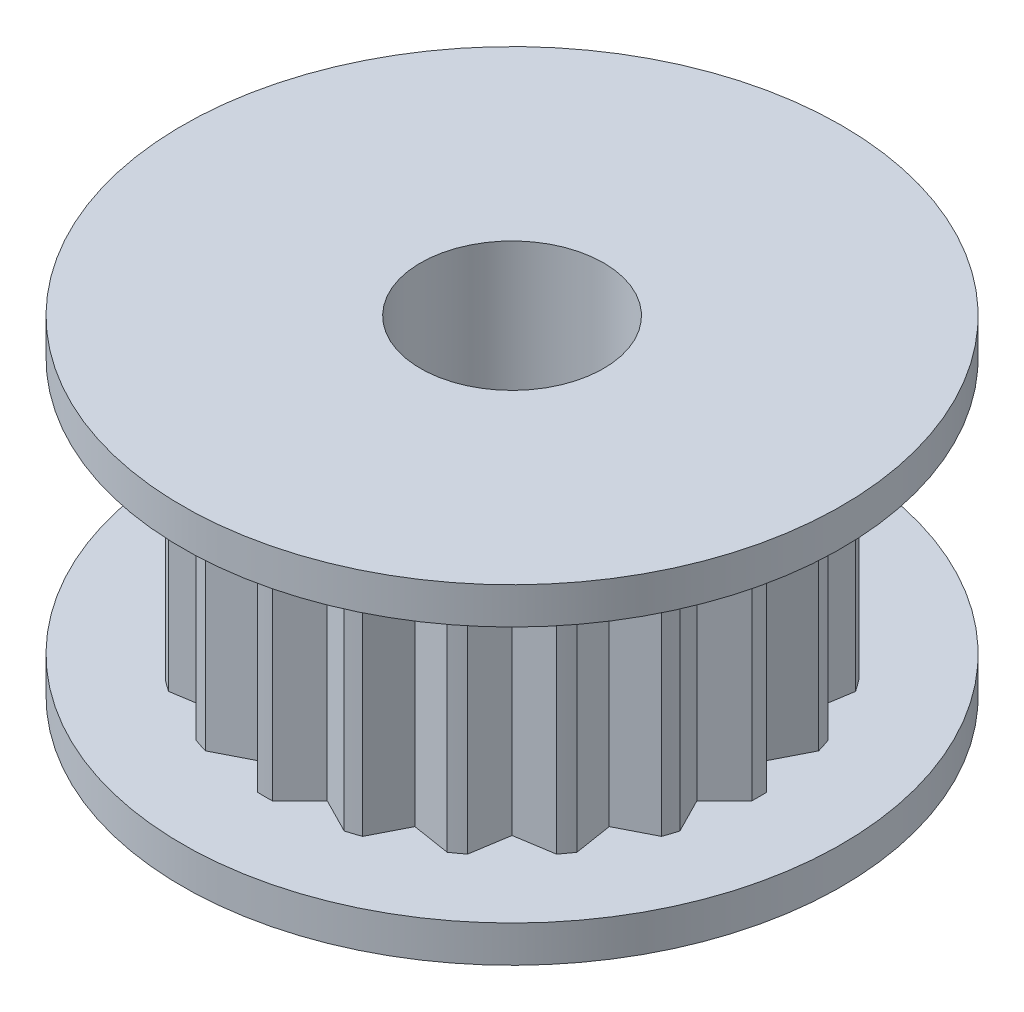
SolidWorks part; units mm, degrees
material "Chrome Stainless Steel"
ref_plane "Front Plane" through (0, 0, 0) normal (0, 0, 1) x (1, 0, 0)
ref_plane "Top Plane" through (0, 0, 0) normal (0, 1, 0) x (1, 0, 0)
ref_plane "Right Plane" through (0, 0, 0) normal (1, 0, 0) x (0, 0, -1)
sketch "Sketch1" plane through (0, 0, 0) normal (0, 0, 1) x (1, 0, 0)
  line L0 (-2.5, 0) -> (-9, 0)
  line L1 (-9, 0) -> (-9, 1)
  line L2 (-9, 1) -> (-6.05, 1)
  line L3 (-6.05, 1) -> (-6.05, 8)
  line L4 (-6.05, 8) -> (-9, 8)
  line L5 (-9, 8) -> (-9, 9)
  line L6 (-9, 9) -> (-2.5, 9)
  line L7 (-2.5, 9) -> (-2.5, 0)
  line L8 (0, 0) -> (0, 9) construction
  dimension "D1" = 9
  dimension "D2" = 7
  dimension "D3" = 2.5
  dimension "D4" = 9
  dimension "D5" = 6.05
revolve "Revolve1" add sketch "Sketch1" angle 360 about L8
sketch "Sketch2" plane through (0, 1, 0) normal (0, 1, 0) x (1, 0, 0)
  line L0 (-6.9468, 0) -> (-5.9468, -1)
  line L1 (-5.9468, -1) -> (-5.9468, 1)
  line L2 (-5.9468, 1) -> (-6.9468, 0)
  line L3 (-5.9468, 0) -> (0, 0) construction
  dimension "D1" = 5.9468
  dimension "D2" = 1
  dimension "D3" = 2
extrude "Boss-Extrude1" add sketch "Sketch2" along normal up to next
pattern_circular "CirPattern1" count 20 over 360 about axis through (0, 0, 0) along (0, 1, 0) of "Boss-Extrude1"
sketch "Sketch3" plane through (0, 1, 0) normal (0, 1, 0) x (1, 0, 0)
  circle A0 centre (0, 0) radius 7.5
  circle A1 centre (0, 0) radius 6.75
  dimension "D1" = 15
  dimension "D2" = 13.5
extrude "Cut-Extrude1" cut sketch "Sketch3" along normal up to surface (7 mm away) up to face at (0, 8, -9)
